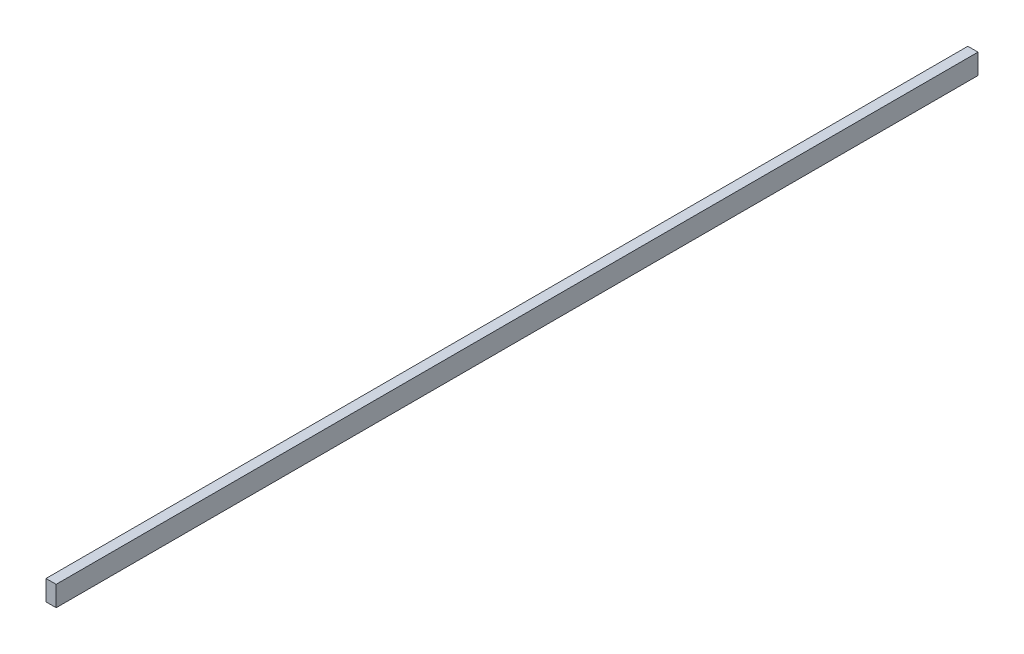
SolidWorks part; units mm, degrees
ref_plane "Front Plane" through (0, 0, 0) normal (0, 0, 1) x (1, 0, 0)
ref_plane "Top Plane" through (0, 0, 0) normal (0, 1, 0) x (1, 0, 0)
ref_plane "Right Plane" through (0, 0, 0) normal (1, 0, 0) x (0, 0, -1)
sketch "Sketch1" plane through (0, 0, 0) normal (0, 0, 1) x (1, 0, 0)
  line L1 (0, 0) -> (3.175, 0)
  line L2 (0, 0) -> (0, 6.35)
  line L3 (0, 6.35) -> (3.175, 6.35)
  line L4 (3.175, 0) -> (3.175, 6.35)
  dimension "D1" = 3.175
  dimension "D2" = 6.35
extrude "Boss-Extrude1" add sketch "Sketch1" along normal blind 288.29
